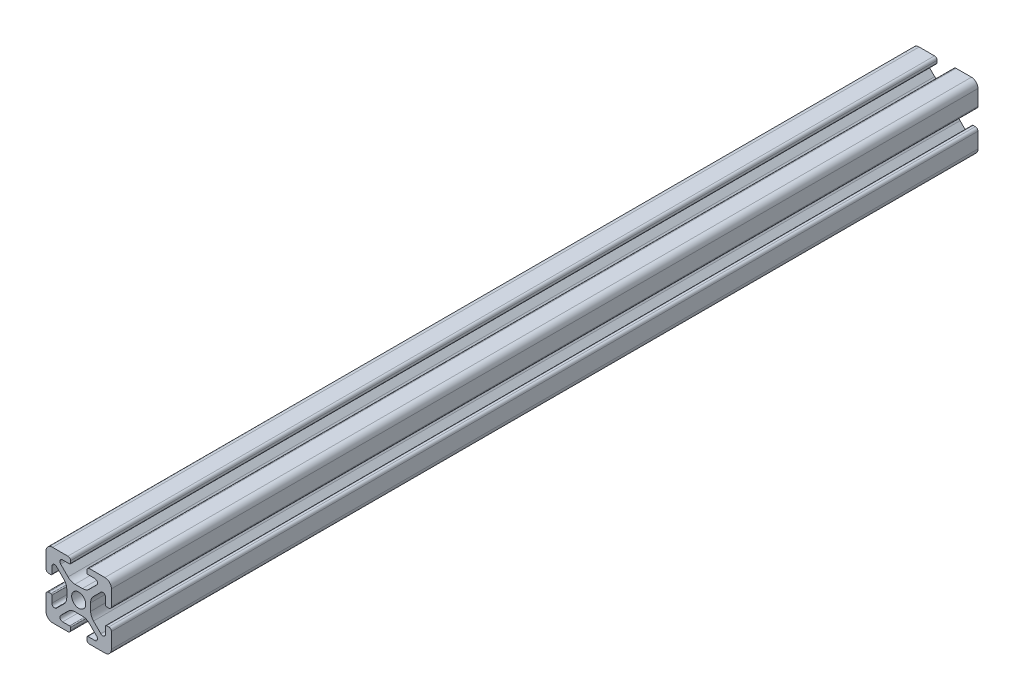
SolidWorks part; units mm, degrees
material "3.0205 (EN-AW 1200)"
ref_plane "Plan de face" through (0, 0, 0) normal (0, 0, 1) x (1, 0, 0)
ref_plane "Plan de dessus" through (0, 0, 0) normal (0, 1, 0) x (1, 0, 0)
ref_plane "Plan de droite" through (0, 0, 0) normal (1, 0, 0) x (0, 0, -1)
ref_plane "Plan1" through (0, 0, 0) normal (0, 0, -1) x (-1, 0, 0)
sketch "Esquisse1" plane through (0, 0, 0) normal (0, 0, -1) x (-1, 0, 0)
  line L0 (-12.5, 0.8) -> (-12.5, 1.5)
  line L1 (-12.8, 1.8) -> (-14.9176, 1.8)
  line L2 (-15.5062, 3.221) -> (-13.2559, 5.4713)
  line L3 (-11.1346, 6.35) -> (-8.8654, 6.35)
  line L4 (-6.7441, 5.4713) -> (-4.4938, 3.221)
  line L5 (-5.0824, 1.8) -> (-7.2, 1.8)
  line L6 (-7.5, 1.5) -> (-7.5, 0.8)
  line L7 (-6.7, 0) -> (-2, 0)
  line L8 (0, 2) -> (0, 6.7)
  line L9 (-0.8, 7.5) -> (-1.5, 7.5)
  line L10 (-1.8, 7.2) -> (-1.8, 5.0824)
  line L11 (-3.221, 4.4938) -> (-5.4713, 6.7441)
  line L12 (-6.35, 8.8654) -> (-6.35, 11.1346)
  line L13 (-5.4713, 13.2559) -> (-3.221, 15.5062)
  line L14 (-1.8, 14.9176) -> (-1.8, 12.8)
  line L15 (-1.5, 12.5) -> (-0.8, 12.5)
  line L16 (0, 13.3) -> (0, 18)
  line L17 (-2, 20) -> (-6.7, 20)
  line L18 (-7.5, 19.2) -> (-7.5, 18.5)
  line L19 (-7.2, 18.2) -> (-5.0824, 18.2)
  line L20 (-4.4938, 16.779) -> (-6.7441, 14.5287)
  line L21 (-8.8654, 13.65) -> (-11.1346, 13.65)
  line L22 (-13.2559, 14.5287) -> (-15.5062, 16.779)
  line L23 (-14.9176, 18.2) -> (-12.8, 18.2)
  line L24 (-12.5, 18.5) -> (-12.5, 19.2)
  line L25 (-13.3, 20) -> (-18, 20)
  line L26 (-20, 18) -> (-20, 13.3)
  line L27 (-19.2, 12.5) -> (-18.5, 12.5)
  line L28 (-18.2, 12.8) -> (-18.2, 14.9176)
  line L29 (-16.779, 15.5062) -> (-14.5287, 13.2559)
  line L30 (-13.65, 11.1346) -> (-13.65, 8.8654)
  line L31 (-14.5287, 6.7441) -> (-16.779, 4.4938)
  line L32 (-18.2, 5.0824) -> (-18.2, 7.2)
  line L33 (-18.5, 7.5) -> (-19.2, 7.5)
  line L34 (-20, 6.7) -> (-20, 2)
  line L35 (-18, 0) -> (-13.3, 0)
  arc A0 (-12.5, 1.5) -> (-12.8, 1.8) centre (-12.8, 1.5) ccw
  arc A1 (-14.9176, 1.8) -> (-15.5062, 3.221) centre (-14.9176, 2.6324) cw
  arc A2 (-13.2559, 5.4713) -> (-11.1346, 6.35) centre (-11.1346, 3.35) cw
  arc A3 (-8.8654, 6.35) -> (-6.7441, 5.4713) centre (-8.8654, 3.35) cw
  arc A4 (-4.4938, 3.221) -> (-5.0824, 1.8) centre (-5.0824, 2.6324) cw
  arc A5 (-7.2, 1.8) -> (-7.5, 1.5) centre (-7.2, 1.5) ccw
  arc A6 (-7.5, 0.8) -> (-6.7, 0) centre (-6.7, 0.8) ccw
  arc A7 (-2, 0) -> (0, 2) centre (-2, 2) ccw
  arc A8 (0, 6.7) -> (-0.8, 7.5) centre (-0.8, 6.7) ccw
  arc A9 (-1.5, 7.5) -> (-1.8, 7.2) centre (-1.5, 7.2) ccw
  arc A10 (-1.8, 5.0824) -> (-3.221, 4.4938) centre (-2.6324, 5.0824) cw
  arc A11 (-5.4713, 6.7441) -> (-6.35, 8.8654) centre (-3.35, 8.8654) cw
  arc A12 (-6.35, 11.1346) -> (-5.4713, 13.2559) centre (-3.35, 11.1346) cw
  arc A13 (-3.221, 15.5062) -> (-1.8, 14.9176) centre (-2.6324, 14.9176) cw
  arc A14 (-1.8, 12.8) -> (-1.5, 12.5) centre (-1.5, 12.8) ccw
  arc A15 (-0.8, 12.5) -> (0, 13.3) centre (-0.8, 13.3) ccw
  arc A16 (0, 18) -> (-2, 20) centre (-2, 18) ccw
  arc A17 (-6.7, 20) -> (-7.5, 19.2) centre (-6.7, 19.2) ccw
  arc A18 (-7.5, 18.5) -> (-7.2, 18.2) centre (-7.2, 18.5) ccw
  arc A19 (-5.0824, 18.2) -> (-4.4938, 16.779) centre (-5.0824, 17.3676) cw
  arc A20 (-6.7441, 14.5287) -> (-8.8654, 13.65) centre (-8.8654, 16.65) cw
  arc A21 (-11.1346, 13.65) -> (-13.2559, 14.5287) centre (-11.1346, 16.65) cw
  arc A22 (-15.5062, 16.779) -> (-14.9176, 18.2) centre (-14.9176, 17.3676) cw
  arc A23 (-12.8, 18.2) -> (-12.5, 18.5) centre (-12.8, 18.5) ccw
  arc A24 (-12.5, 19.2) -> (-13.3, 20) centre (-13.3, 19.2) ccw
  arc A25 (-18, 20) -> (-20, 18) centre (-18, 18) ccw
  arc A26 (-20, 13.3) -> (-19.2, 12.5) centre (-19.2, 13.3) ccw
  arc A27 (-18.5, 12.5) -> (-18.2, 12.8) centre (-18.5, 12.8) ccw
  arc A28 (-18.2, 14.9176) -> (-16.779, 15.5062) centre (-17.3676, 14.9176) cw
  arc A29 (-14.5287, 13.2559) -> (-13.65, 11.1346) centre (-16.65, 11.1346) cw
  arc A30 (-13.65, 8.8654) -> (-14.5287, 6.7441) centre (-16.65, 8.8654) cw
  arc A31 (-16.779, 4.4938) -> (-18.2, 5.0824) centre (-17.3676, 5.0824) cw
  arc A32 (-18.2, 7.2) -> (-18.5, 7.5) centre (-18.5, 7.2) ccw
  arc A33 (-19.2, 7.5) -> (-20, 6.7) centre (-19.2, 6.7) ccw
  arc A34 (-20, 2) -> (-18, 0) centre (-18, 2) ccw
  arc A35 (-13.3, 0) -> (-12.5, 0.8) centre (-13.3, 0.8) ccw
  circle A36 centre (-10, 10) radius 2.15
extrude "Boss.-Extru.1" add sketch "Esquisse1" against normal blind 265
